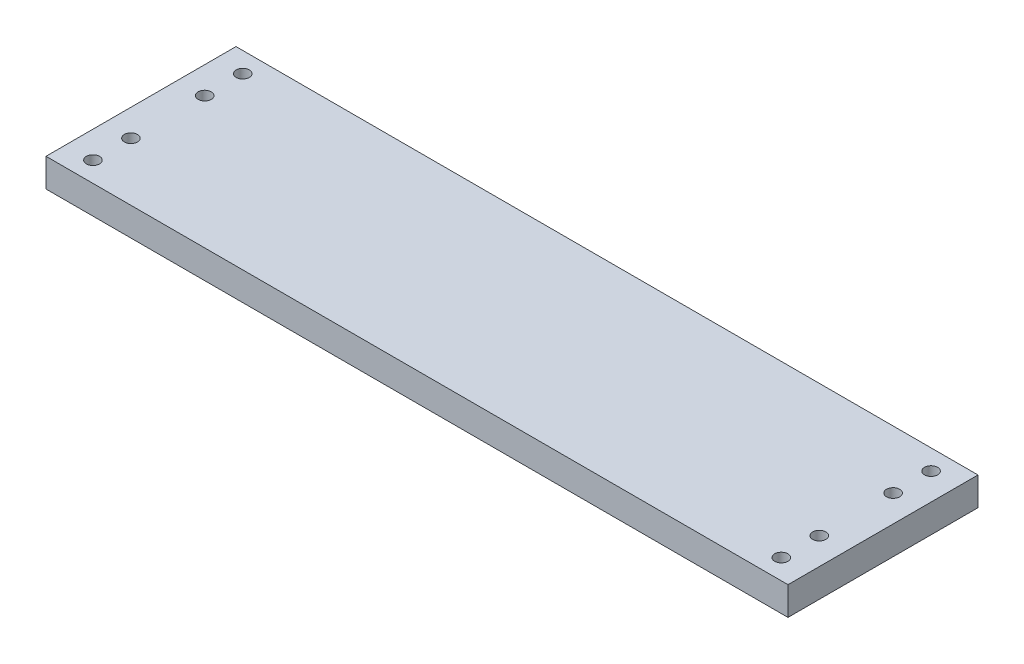
SolidWorks part; units mm, degrees
ref_plane "Front Plane" through (0, 0, 0) normal (0, 0, 1) x (1, 0, 0)
ref_plane "Top Plane" through (0, 0, 0) normal (0, 1, 0) x (1, 0, 0)
ref_plane "Right Plane" through (0, 0, 0) normal (1, 0, 0) x (0, 0, -1)
sketch "Sketch1" plane through (0, 0, 0) normal (0, 1, 0) x (1, 0, 0)
  line L1 (-83, 21.255) -> (83, 21.255)
  line L2 (-83, 21.255) -> (-83, -21.255)
  line L3 (-83, -21.255) -> (83, -21.255)
  line L4 (83, 21.255) -> (83, -21.255)
  line L5 (-83, 21.255) -> (83, -21.255) construction
  line L6 (-83, -21.255) -> (83, 21.255) construction
  point P0 (0, 0)
  dimension "2.25" = 42.51
  dimension "D2" = 166
extrude "Boss-Extrude1" add sketch "Sketch1" along normal blind 6.35 contours L2 L3 L4 L1
sketch "Sketch2" plane through (0, 6.35, 0) normal (0, 1, 0) x (1, 0, 0)
  line L0 (-77, 16.755) -> (0, 16.755)
  line L1 (0, 16.755) -> (77, 16.755)
  line L5 (77, 8.255) -> (0, 8.255)
  line L6 (0, 8.255) -> (-77, 8.255)
  line L7 (-77, 8.255) -> (-77, 16.755)
  line L10 (0, 0) -> (0, 8.255) construction
  line L11 (0, 16.755) -> (0, 8.255) construction
  line L12 (77, 16.755) -> (77, 8.255)
  dimension "D1" = 77
  dimension "D2" = 8.255
  dimension "D6" = 8.5
hole_wizard "#4 Clearance Hole1" positions "Sketch3" profile "Sketch5" hole size "#4" standard "ANSI Inch" end condition through all
sketch "Sketch3" plane through (0, 6.35, 0) normal (0, 1, 0) x (1, 0, 0)
  point P0 (-77, 8.255)
  point P2 (-77, 16.755)
  point P8 (77, 8.255)
  point P10 (77, 16.755)
sketch "Sketch5" plane through (-77, 6.35, -8.255) normal (1, 0, 0) x (0, 0, 1)
  line L0 (0, 0) -> (0, 6.35)
  line L1 (0, 6.35) -> (1.4732, 6.35)
  line L2 (1.4732, 6.35) -> (1.4732, 0)
  line L5 (1.4732, 0) -> (0, 0)
  line L11 (0, -6.35) -> (0, 107.95) construction
  dimension "Thru Hole Dia." = 2.9464
  dimension "Thru Hole Depth" = 6.35
sketch "Sketch6" plane through (0, 0, 0) normal (0, -1, 0) x (1, 0, 0)
  line L1 (-78.8331, -19.93) -> (-75.1669, -19.93)
  line L2 (-75.1669, -19.93) -> (-73.3338, -16.755)
  line L3 (-73.3338, -16.755) -> (-75.1669, -13.58)
  line L4 (-75.1669, -13.58) -> (-78.8331, -13.58)
  line L5 (-78.8331, -13.58) -> (-80.6662, -16.755)
  line L6 (-80.6662, -16.755) -> (-78.8331, -19.93)
  line L7 (-78.8331, -5.08) -> (-80.6662, -8.255)
  line L8 (-80.6662, -8.255) -> (-78.8331, -11.43)
  line L9 (-78.8331, -11.43) -> (-75.1669, -11.43)
  line L10 (-75.1669, -11.43) -> (-73.3338, -8.255)
  line L11 (-73.3338, -8.255) -> (-75.1669, -5.08)
  line L12 (-75.1669, -5.08) -> (-78.8331, -5.08)
  line L25 (78.8331, -11.43) -> (80.6662, -8.255)
  line L26 (80.6662, -8.255) -> (78.8331, -5.08)
  line L27 (78.8331, -5.08) -> (75.1669, -5.08)
  line L28 (75.1669, -5.08) -> (73.3338, -8.255)
  line L29 (73.3338, -8.255) -> (75.1669, -11.43)
  line L30 (75.1669, -11.43) -> (78.8331, -11.43)
  line L31 (78.8331, -19.93) -> (80.6662, -16.755)
  line L32 (80.6662, -16.755) -> (78.8331, -13.58)
  line L33 (78.8331, -13.58) -> (75.1669, -13.58)
  line L34 (75.1669, -13.58) -> (73.3338, -16.755)
  line L35 (73.3338, -16.755) -> (75.1669, -19.93)
  line L36 (75.1669, -19.93) -> (78.8331, -19.93)
  circle A0 centre (-77, -16.755) radius 3.175 construction
  circle A1 centre (-77, -8.255) radius 3.175 construction
  circle A4 centre (77, -8.255) radius 3.175 construction
  circle A5 centre (77, -16.755) radius 3.175 construction
  dimension "D1" = 6.35
hole_wizard "CSK for #4 Flat Head Socket Cap Screw1" positions "Sketch7" profile "Sketch8" countersink size "#4" standard "ANSI Inch" end condition through all
sketch "Sketch7" plane through (0, 0, 0) normal (0, -1, 0) x (-1, 0, 0)
  point P0 (77, 8.255)
  point P3 (77, 16.755)
  point P6 (-77, 8.255)
  point P9 (-77, 16.755)
sketch "Sketch8" plane through (-77, 0, -8.255) normal (1, 0, 0) x (0, 0, -1)
  line L0 (0, 0) -> (0, 6.35)
  line L1 (0, 6.35) -> (1.4732, 6.35)
  line L2 (1.4732, 6.35) -> (1.4732, 2.7927)
  line L3 (1.4732, 2.7927) -> (3.9009, 0)
  line L5 (3.9009, 0) -> (0, 0)
  line L6 (-1.4732, 2.7927) -> (-3.9009, 0) construction
  line L11 (0, -6.35) -> (0, 107.95) construction
  dimension "Thru Hole Dia." = 2.9464
  dimension "Thru Hole Depth" = 6.35
  dimension "Near C'Sink Dia." = 7.8018
  dimension "Near C'Sink Angle" = 82
mirror "Mirror1" about plane through (0, 0, 0) normal (0, 0, 1) of "CSK for #4 Flat Head Socket Cap Screw1"
